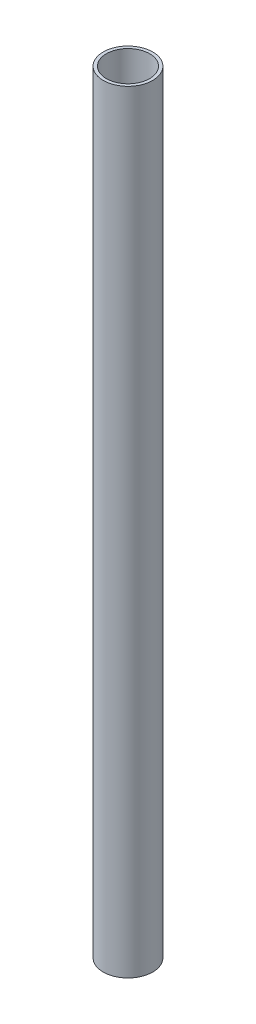
SolidWorks part; units mm, degrees
ref_plane "前视基准面" through (0, 0, 0) normal (0, 0, 1) x (1, 0, 0)
ref_plane "上视基准面" through (0, 0, 0) normal (0, 1, 0) x (1, 0, 0)
ref_plane "右视基准面" through (0, 0, 0) normal (1, 0, 0) x (0, 0, -1)
other "Configuration Table"
sketch "草图1" plane through (0, 0, 0) normal (0, 1, 0) x (1, 0, 0)
  circle A0 centre (0, 0) radius 8
  circle A1 centre (0, 0) radius 7
  dimension "D1" = 16
  dimension "D2" = 14
extrude "凸台-拉伸1" add sketch "草图1" along normal blind 250
